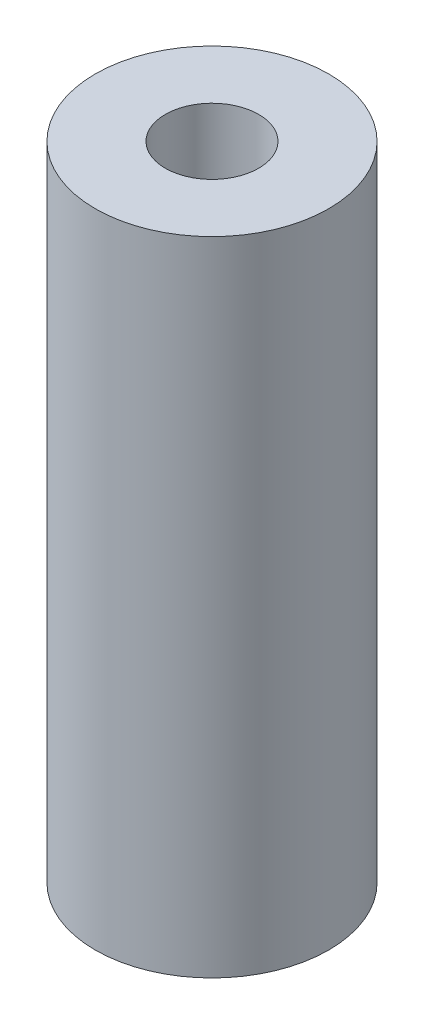
SolidWorks part; units mm, degrees
ref_plane "Front Plane" through (0, 0, 0) normal (0, 0, 1) x (1, 0, 0)
ref_plane "Top Plane" through (0, 0, 0) normal (0, 1, 0) x (1, 0, 0)
ref_plane "Right Plane" through (0, 0, 0) normal (1, 0, 0) x (0, 0, -1)
sketch "Sketch1" plane through (0, 0, 0) normal (0, 1, 0) x (1, 0, 0)
  circle A0 centre (0, 0) radius 6
  dimension "D1" = 12
extrude "Boss-Extrude1" add sketch "Sketch1" along normal blind 33
hole_wizard "M4 Clearance Hole1" positions "3DSketch1" profile "Sketch2" hole size "M4" standard "DIN" end condition through all
sketch3d "3DSketch1"
  line L0 (0, 33, 0) -> (0, 0, 0) construction
  point P0 (0, 33, 0)
sketch "Sketch2" plane through (0, 33, 0) normal (1, 0, 0) x (0, 0, 1)
  line L0 (0, 0) -> (0, 33)
  line L1 (0, 33) -> (2.4, 33)
  line L2 (2.4, 33) -> (2.4, 0)
  line L5 (2.4, 0) -> (0, 0)
  line L11 (0, -6.35) -> (0, 107.95) construction
  dimension "Thru Hole Dia." = 4.8
  dimension "Thru Hole Depth" = 33
